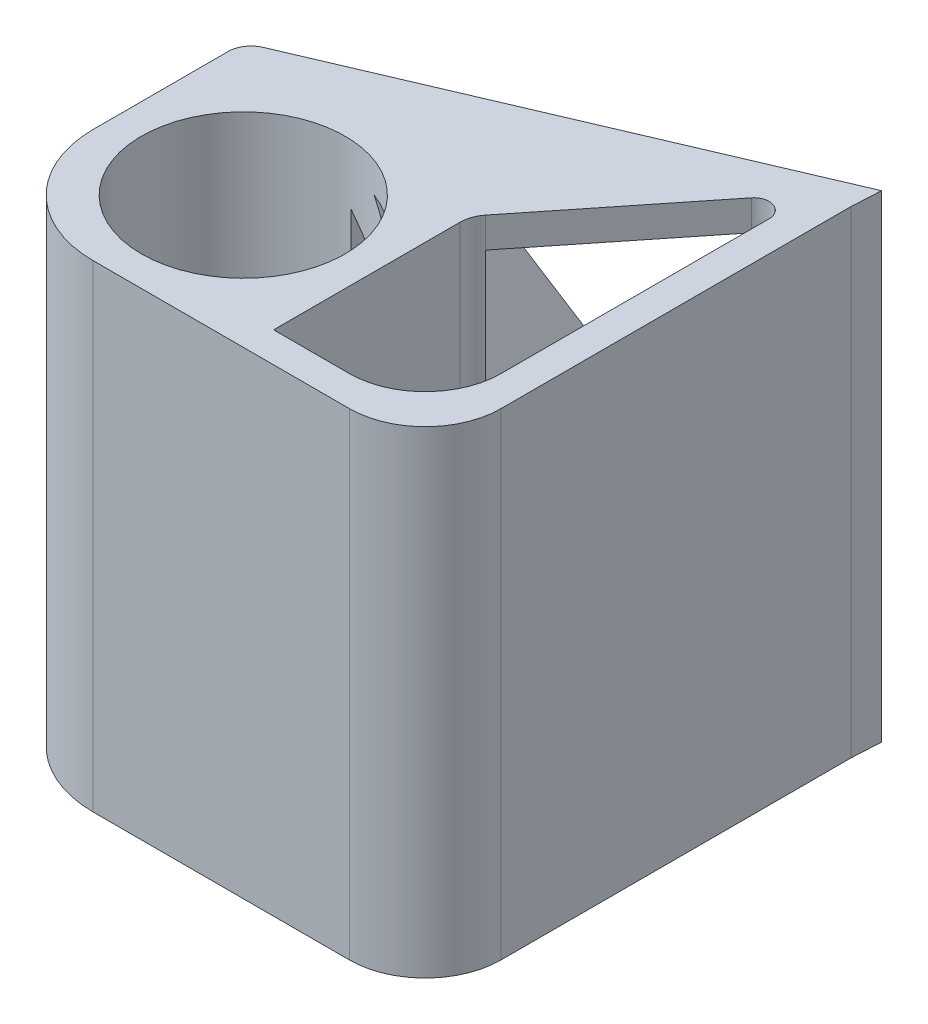
SolidWorks part; units mm, degrees
ref_plane "Front Plane" through (0, 0, 0) normal (0, 0, 1) x (1, 0, 0)
ref_plane "Top Plane" through (0, 0, 0) normal (0, 1, 0) x (1, 0, 0)
ref_plane "Right Plane" through (0, 0, 0) normal (1, 0, 0) x (0, 0, -1)
sketch "Sketch2" plane through (0, 0, 0) normal (0, 1, 0) x (1, 0, 0)
  line L1 (-17.4, -17.4) -> (17.4, -17.4)
  line L2 (-17.4, -17.4) -> (-17.4, 17.4)
  line L5 (0, 17.4) -> (0, -17.4) construction
  line L6 (-17.4, 0) -> (17.4, 12.6) construction
  line L8 (17.4, -13.4) -> (17.4, 11.2002)
  line L13 (18.2728, 13.6944) -> (33.8364, 33.208)
  line L14 (41.6153, 42.6051) -> (-17.4, 17.4)
  line L20 (37.4, -3.4) -> (37.4, 31.9609)
  line L24 (27.4, -13.4) -> (17.4, -13.4)
  line L25 (41.4, 38.7812) -> (41.4, -7.4)
  line L26 (31.4, -17.4) -> (17.4, -17.4)
  line L27 (41.4, 38.7812) -> (41.6153, 42.6051)
  circle A0 centre (0, 0) radius 13.45
  arc A1 (31.4, -17.4) -> (41.4, -7.4) centre (31.4, -7.4) ccw
  arc A2 (37.4, -3.4) -> (27.4, -13.4) centre (27.4, -3.4) cw
  arc A3 (18.2728, 13.6944) -> (17.4, 11.2002) centre (21.4, 11.2002) ccw
  arc A4 (37.4, 31.9609) -> (33.8364, 33.208) centre (35.4, 31.9609) ccw
  point P0 (0, 0)
  dimension "D3" = 26.9
  dimension "D8" = 17.4
  dimension "D9" = 17.4
  dimension "D10" = 4
  dimension "D15" = 26
  dimension "D4" = 10
  dimension "D6" = 4
  dimension "D7" = 2
  dimension "D1" = 34.8
  dimension "D2" = 34.8
  dimension "D5" = 20
  dimension "D14" = 4
extrude "Boss-Extrude1" add sketch "Sketch2" along normal blind 59 and the other way blind 4
fillet "Fillet1" radius 15 1 edges at (-17.4, 27.5, 17.4)
fillet "Fillet2" radius 3 1 edges at (-17.4, 27.5, -17.4)
sketch "Sketch3" plane through (-8.9693, 0, -21.0007) normal (-0.3928, 0, -0.9196) x (-0.9196, 0, 0.3928)
  line L0 (-55.005, -4) -> (7.1866, -4) construction
  line L1 (-47.7748, 0) -> (-9.2351, 0)
  line L2 (-51.005, 3.948) -> (-51.005, 51.052)
  line L3 (-47.7748, 55) -> (-9.2351, 55)
  line L4 (-6.005, 3.948) -> (-6.005, 51.052)
  line L5 (-51.005, 0) -> (-6.005, 55) construction
  line L6 (-51.005, 55) -> (-6.005, 0) construction
  line L7 (-55.005, 59) -> (7.1866, 59) construction
  line L8 (-55.005, -4) -> (-55.005, 59) construction
  line L9 (-51.005, 3.948) -> (-31.7351, 27.5)
  line L11 (-6.005, 51.052) -> (-25.2748, 27.5)
  line L13 (-28.505, 23.552) -> (-47.7748, 0)
  line L14 (-28.505, 31.448) -> (-9.2351, 55)
  line L15 (-51.005, 51.052) -> (-31.7351, 27.5)
  line L17 (-6.005, 3.948) -> (-25.2748, 27.5)
  line L18 (-28.505, 23.552) -> (-9.2351, 0)
  line L19 (-28.505, 31.448) -> (-47.7748, 55)
  line L20 (-51.005, 51.052) -> (-51.005, 55) construction
  line L21 (-47.7748, 55) -> (-51.005, 55) construction
  line L22 (-9.2351, 55) -> (-6.005, 55) construction
  line L23 (-6.005, 55) -> (-6.005, 51.052) construction
  line L24 (-9.2351, 0) -> (-6.005, 0) construction
  line L25 (-6.005, 0) -> (-6.005, 3.948) construction
  line L26 (-51.005, 3.948) -> (-51.005, 0) construction
  line L27 (-51.005, 0) -> (-47.7748, 0) construction
  line L28 (-9.2351, 55) -> (-6.005, 51.052) construction
  line L29 (-6.005, 51.052) -> (-9.2351, 55) construction
  line L30 (-51.005, 3.948) -> (-47.7748, 0) construction
  line L31 (-6.005, 3.948) -> (-9.2351, 0) construction
  line L32 (-47.7748, 55) -> (-51.005, 51.052) construction
  point P0 (-43.7941, 23.9127)
  point P1 (-28.505, 27.5)
  point P2 (-49.3899, 53.026)
  point P3 (-7.6201, 1.974)
  point P4 (-49.3899, 1.974)
  point P13 (-7.6201, 53.026)
  point P31 (-28.505, 27.5)
  dimension "D1" = 4
  dimension "D2" = 4
  dimension "D3" = 4
  dimension "D4" = 45
  dimension "D5" = 5
  dimension "D6" = 5
extrude "Cut-Extrude1" cut sketch "Sketch3" against normal up to surface and the other way through all up to face at (26.0546, 27.5, -23.4512)
sketch "Sketch4" plane through (-8.9693, 0, -21.0007) normal (-0.3928, 0, -0.9196) x (-0.9196, 0, 0.3928)
  line L0 (-51.005, 3.948) -> (-47.7748, 0) construction
  line L1 (-6.005, 3.948) -> (-9.2351, 0) construction
  line L2 (-9.2351, 55) -> (-6.005, 51.052) construction
  line L3 (-51.005, 51.052) -> (-47.7748, 55) construction
  circle A0 centre (-49.3899, 1.974) radius 1.4
  circle A1 centre (-7.6201, 1.974) radius 1.4
  circle A2 centre (-7.6201, 53.026) radius 1.4
  circle A3 centre (-49.3899, 53.026) radius 1.4
  dimension "D1" = 2.8
  dimension "D2" = 2.8
  dimension "D3" = 2.8
  dimension "D4" = 2.8
extrude "Cut-Extrude2" cut sketch "Sketch4" against normal blind 9
